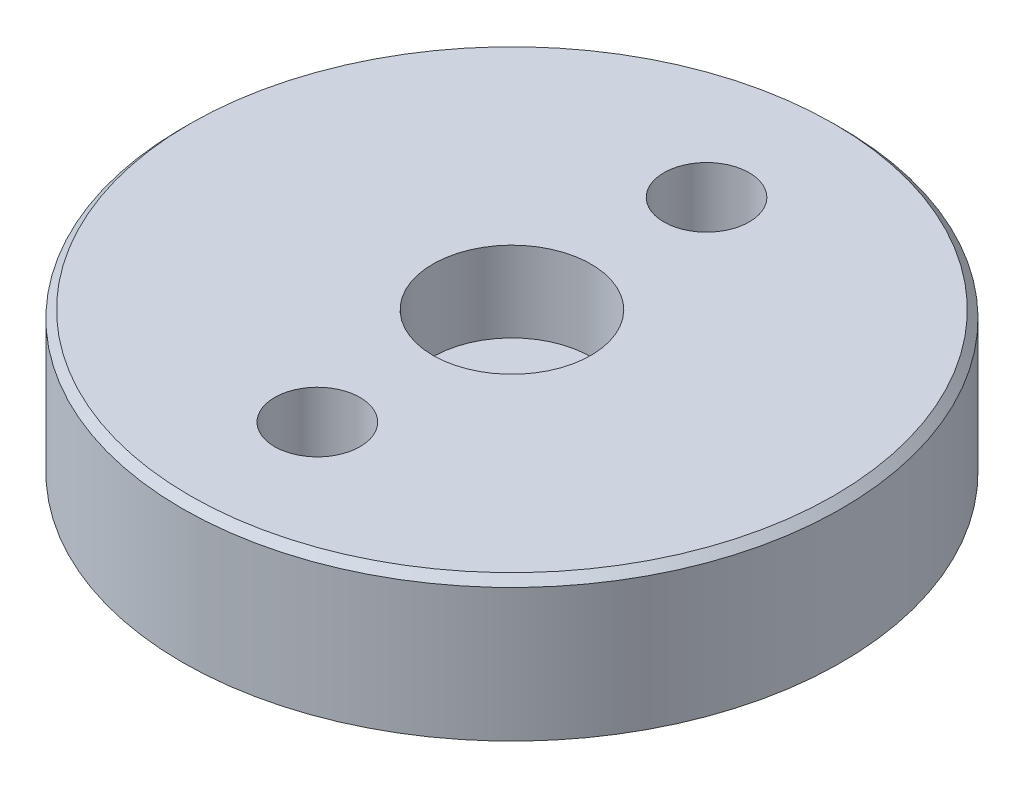
SolidWorks part; units mm, degrees
material "PETG"
ref_plane "Front Plane" through (0, 0, 0) normal (0, 0, 1) x (1, 0, 0)
ref_plane "Top Plane" through (0, 0, 0) normal (0, 1, 0) x (1, 0, 0)
ref_plane "Right Plane" through (0, 0, 0) normal (1, 0, 0) x (0, 0, -1)
sketch "Sketch8" plane through (0, -463.2755, 0) normal (0, 1, 0) x (0.3279, 0, 0.9447)
  circle A0 centre (0, 0) radius 13.125
  dimension "D1" = 26.25
extrude "Boss-Extrude2" add sketch "Sketch8" against normal blind 5.6
sketch "Sketch9" plane through (0, -468.8755, 0) normal (0, -1, 0) x (-1, 0, 0)
  circle A0 centre (0, 0) radius 11.125
  dimension "D1" = 22.25
extrude "Cut-Extrude4" cut sketch "Sketch9" against normal blind 1
sketch "Sketch10" plane through (0, -463.2755, 0) normal (0, 1, 0) x (1, 0, 0)
  circle A0 centre (0, 0) radius 3.15
  dimension "D1" = 6.3
extrude "Cut-Extrude5" cut sketch "Sketch10" against normal blind 3.2
chamfer "Chamfer2" distance 0.3 angle 45 1 edges at (0, -463.2755, 13.125)
sketch "Sketch11" plane through (0, -463.2755, 0) normal (0, 1, 0) x (1, 0, 0)
  line L0 (13.125, 0) -> (-13.125, 0) construction
  line L1 (0, 13.125) -> (0, -13.125) construction
  circle A0 centre (0, 0) radius 7.75 construction
  circle A1 centre (0, 0) radius 13.125 construction
  circle A2 centre (0, -7.75) radius 1.7
  circle A3 centre (0, 7.75) radius 1.7
  dimension "D1" = 15.5
  dimension "D2" = 3.4
extrude "Cut-Extrude6" cut sketch "Sketch11" against normal through all
sketch "Sketch12" plane through (0, -463.2755, 0) normal (0, 1, 0) x (1, 0, 0)
  line L0 (0, -12.825) -> (0, 12.825) construction
  circle A0 centre (0, 0) radius 12.825 construction
equation "\"D1@Sketch8\"=\"MAG_SeatOD\""
equation "\"D1@Boss-Extrude2\"=\"MAG_SeatThk\""
equation "\"D1@Sketch9\"=\"MAG_SeatPocketForNestDia\""
equation "\"D1@Cut-Extrude4\"=\"MAG_SeatPocketForNestDepth\""
equation "\"D1@Sketch10\"=\"MAG_SeatPocketDia\""
equation "\"D1@Cut-Extrude5\"=\"MAG_SeatPocketDepth\""
equation "\"D1@Chamfer2\"= \"MAG_SeatPocketChamfer\""
equation "\"D1@Sketch11\"=\"SEAT_ScrewBCDia\""
equation "\"D2@Sketch11\"=\"SEAT_ScrewClearDia\""
equation "\"____ VERSION / MIRROR CONTROL ____\" = 0"
equation "\"SYS_VersionTag\" = 2.00"
equation "\"SYS_MagnetMountMode\" = 1"
equation "\"____ FIXED SHAFT / INNER-RING HARDWARE ____\" = 0"
equation "\"SFT_ShaftDiameter\" = 8mm"
equation "\"____ COUPLER + EXTENSION (WITH INTERNAL GAP) ____\" = 0"
equation "\"EXT_Dia\" = \"SFT_ShaftDiameter\""
equation "\"____ ADAPTER COLLAR ON EXTENSION (COLLAR #3, NON-MAGNETIC) ____\" = 0"
equation "\"ADP_CollarOD\" = 22mm"
equation "\"____ MAGNET + SEAT GEOMETRY ____\" = 0"
equation "\"MAG_MagnetDia\" = 6mm"
equation "\"MAG_MagnetThk\" = 3mm"
equation "\"SEAT_PocketClear_Dia\" = 0.25mm"
equation "\"CPL_OD\" = 20mm"
equation "\"SEAT_NestOD\" = IIF(\"SYS_MagnetMountMode\" > 0, \"ADP_CollarOD\", \"CPL_OD\")"
equation "\"MAG_SeatPocketForNestDia\" = \"SEAT_NestOD\" + \"SEAT_PocketClear_Dia\""
equation "\"MAG_SeatPocketForNestDepth\" = 1.0mm"
equation "\"SEAT_WallThk\" = 2.0mm"
equation "\"SEAT_MountScrewCount\" = 2"
equation "\"SEAT_ScrewClearDia\" = 3.4mm"
equation "\"MAG_SeatFitClear_Rad\" = 0.15mm"
equation "\"MAG_SeatPocketDia\" = \"MAG_MagnetDia\" + 2*\"MAG_SeatFitClear_Rad\""
equation "\"MAG_SeatGlueMargin\" = 0.20mm"
equation "\"MAG_SeatPocketDepth\" = \"MAG_MagnetThk\" + \"MAG_SeatGlueMargin\""
equation "\"MAG_SeatPocketChamfer\" = 0.30mm"
equation "\"MAG_SeatFloorThk\" = 1.4mm"
equation "\"MAG_SeatThk\" = \"MAG_SeatPocketDepth\" + \"MAG_SeatPocketForNestDepth\" + \"MAG_SeatFloorThk\""
equation "\"MAG_SeatOD\" = \"MAG_SeatPocketForNestDia\" + 2*\"SEAT_WallThk\""
equation "\"____ BOLT CIRCLE (ROBUST: LIMIT BY METAL OD AND BORE) ____\" = 0"
equation "\"CPL_BoreDia\" = \"EXT_Dia\""
equation "\"SEAT_NestBoreDia\" = IIF(\"SYS_MagnetMountMode\" > 0, \"EXT_Dia\", \"CPL_BoreDia\")"
equation "\"SEAT_TapDrillDia\" = 2.5mm"
equation "\"SEAT_BoreWallMin\" = 2.0mm"
equation "\"SEAT_MetalOuterEdgeMin\" = 1.5mm"
equation "\"SEAT_PlasticOuterEdgeMin\" = 1.5mm"
equation "\"SEAT_BoltR_Min\" = (\"SEAT_NestBoreDia\" / 2) + (\"SEAT_TapDrillDia\" / 2) + \"SEAT_BoreWallMin\""
equation "\"SEAT_MetalOD\" = IIF(\"SYS_MagnetMountMode\" > 0, \"ADP_CollarOD\", \"CPL_OD\")"
equation "\"SEAT_BoltR_MaxMetal\" = (\"SEAT_MetalOD\" / 2) - (\"SEAT_TapDrillDia\" / 2) - \"SEAT_MetalOuterEdgeMin\""
equation "\"SEAT_BoltR_MaxSeat\" = (\"MAG_SeatOD\" / 2) - (\"SEAT_ScrewClearDia\" / 2) - \"SEAT_PlasticOuterEdgeMin\""
equation "\"SEAT_BoltR_Max\" = IIF(\"SEAT_BoltR_MaxMetal\" < \"SEAT_BoltR_MaxSeat\", \"SEAT_BoltR_MaxMetal\", \"SEAT_BoltR_MaxSeat\")"
equation "\"SEAT_BoltR_Target\" = (\"SEAT_BoltR_Min\" + \"SEAT_BoltR_Max\") / 2"
equation "\"SEAT_ScrewBCDia\" = 2*\"SEAT_BoltR_Target\""
